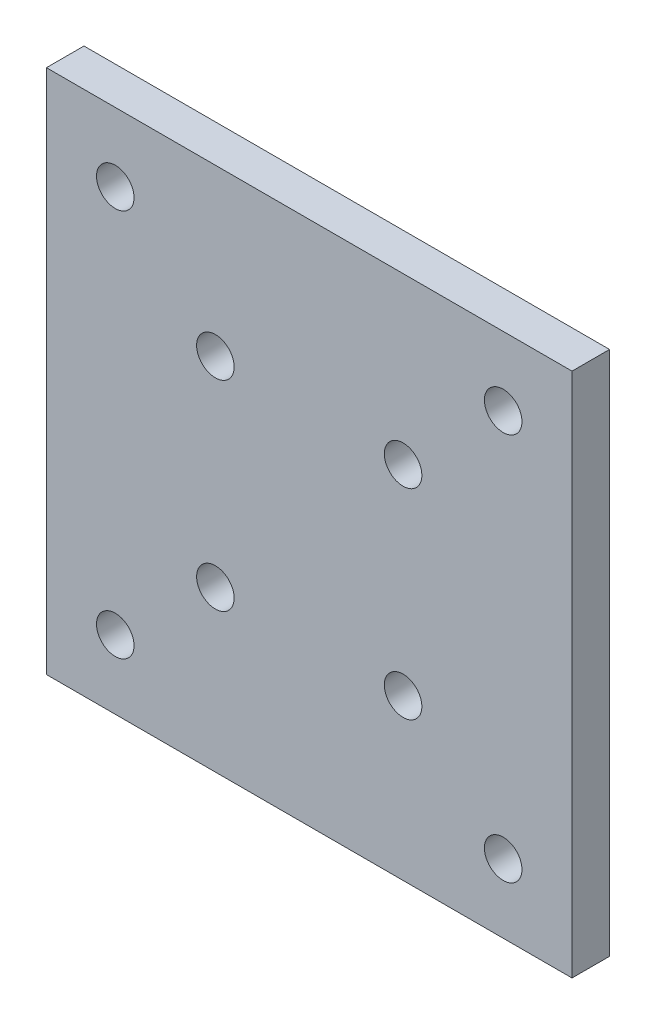
SolidWorks part; units mm, degrees
ref_plane "Front Plane" through (0, 0, 0) normal (0, 0, 1) x (1, 0, 0)
ref_plane "Top Plane" through (0, 0, 0) normal (0, 1, 0) x (1, 0, 0)
ref_plane "Right Plane" through (0, 0, 0) normal (1, 0, 0) x (0, 0, -1)
sketch "Sketch1" plane through (0, 0, 0) normal (0, 0, 1) x (1, 0, 0)
  line L0 (-6.7577, 36.5) -> (54.4268, 36.5) construction
  line L1 (0, 0) -> (42, 0)
  line L2 (0, 0) -> (0, 42)
  line L3 (0, 42) -> (42, 42)
  line L4 (42, 0) -> (42, 42)
  line L5 (-6.7577, 5.5) -> (54.4268, 5.5) construction
  line L6 (21, 47.3496) -> (21, -17.2823) construction
  line L7 (8.8163, 28.7841) -> (28.3531, 28.7841) construction
  line L8 (8.8163, 12.7841) -> (28.3531, 12.7841) construction
  circle A0 centre (5.5, 36.5) radius 1.5
  circle A1 centre (36.5, 36.5) radius 1.5
  circle A2 centre (36.5, 5.5) radius 1.5
  circle A3 centre (5.5, 5.5) radius 1.5
  circle A4 centre (13.5, 28.7841) radius 1.5
  circle A5 centre (28.5, 28.7841) radius 1.5
  circle A6 centre (28.5, 12.7841) radius 1.5
  circle A7 centre (13.5, 12.7841) radius 1.5
  point P13 (21, 42)
  dimension "D5" = 5.5
  dimension "D9" = 7.5
  dimension "D10" = 2
  dimension "D1" = 42
  dimension "D2" = 42
  dimension "D3" = 31
  dimension "D4" = 5.5
  dimension "D8" = 16
  dimension "D6" = 2
  dimension "D7" = 2
  dimension "D11" = 2
extrude "Boss-Extrude1" add sketch "Sketch1" along normal blind 3
